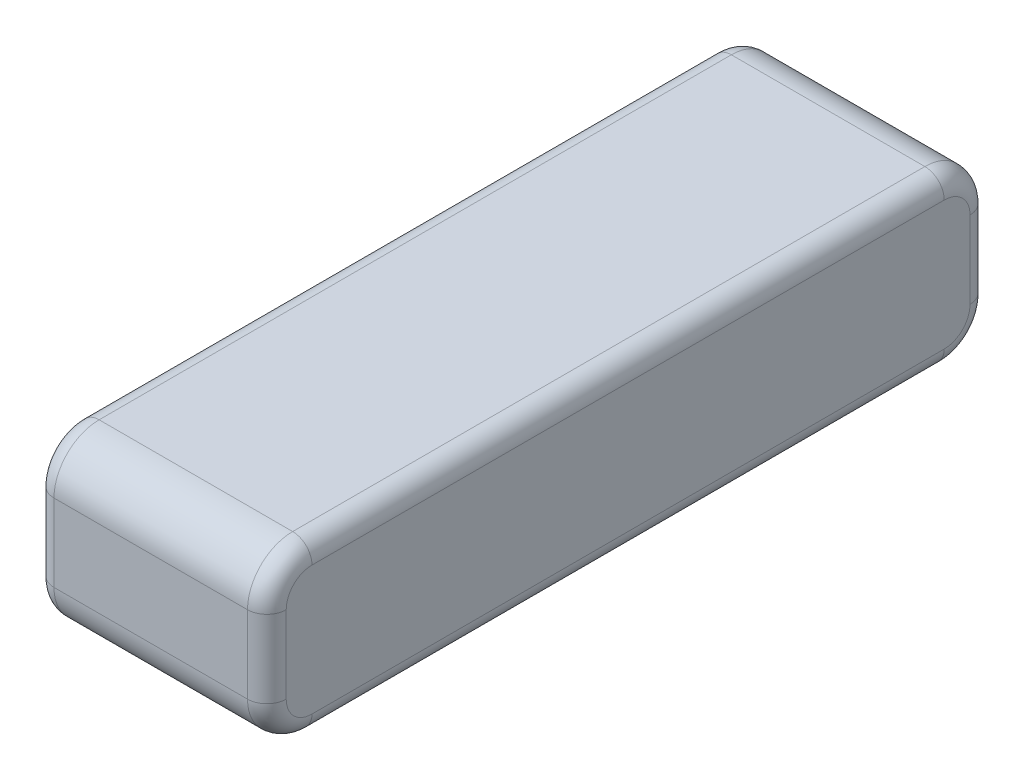
SolidWorks part; units mm, degrees
ref_plane "Front Plane" through (0, 0, 0) normal (0, 0, 1) x (1, 0, 0)
ref_plane "Top Plane" through (0, 0, 0) normal (0, 1, 0) x (1, 0, 0)
ref_plane "Right Plane" through (0, 0, 0) normal (1, 0, 0) x (0, 0, -1)
sketch "Sketch1" plane through (0, 0, 0) normal (1, 0, 0) x (0, 0, -1)
  line L0 (-49, 6) -> (49, -6) construction
  line L1 (-49, 13) -> (49, 13)
  line L2 (-56, 6) -> (-56, -6)
  line L3 (-49, -13) -> (49, -13)
  line L4 (56, 6) -> (56, -6)
  arc A0 (49, 13) -> (56, 6) centre (49, 6) cw
  arc A1 (49, -13) -> (56, -6) centre (49, -6) ccw
  arc A2 (-56, -6) -> (-49, -13) centre (-49, -6) ccw
  arc A3 (-49, 13) -> (-56, 6) centre (-49, 6) ccw
  dimension "D3" = 7
  dimension "D1" = 112
  dimension "D2" = 26
extrude "Boss-Extrude1" add sketch "Sketch1" along normal mid plane 36
fillet "Fillet1" radius 3 16 edges at (-18, 13, 0) (-18, 10.9497, 53.9497) (-18, 0, 56) (-18, -10.9497, 53.9497) (-18, -13, 0) (-18, -10.9497, -53.9497) (-18, 0, -56) (-18, 10.9497, -53.9497) (18, 0, -56) (18, -10.9497, -53.9497) (18, -13, 0) (18, -10.9497, 53.9497) (18, 0, 56) (18, 10.9497, 53.9497) (18, 13, 0) (18, 10.9497, -53.9497)
